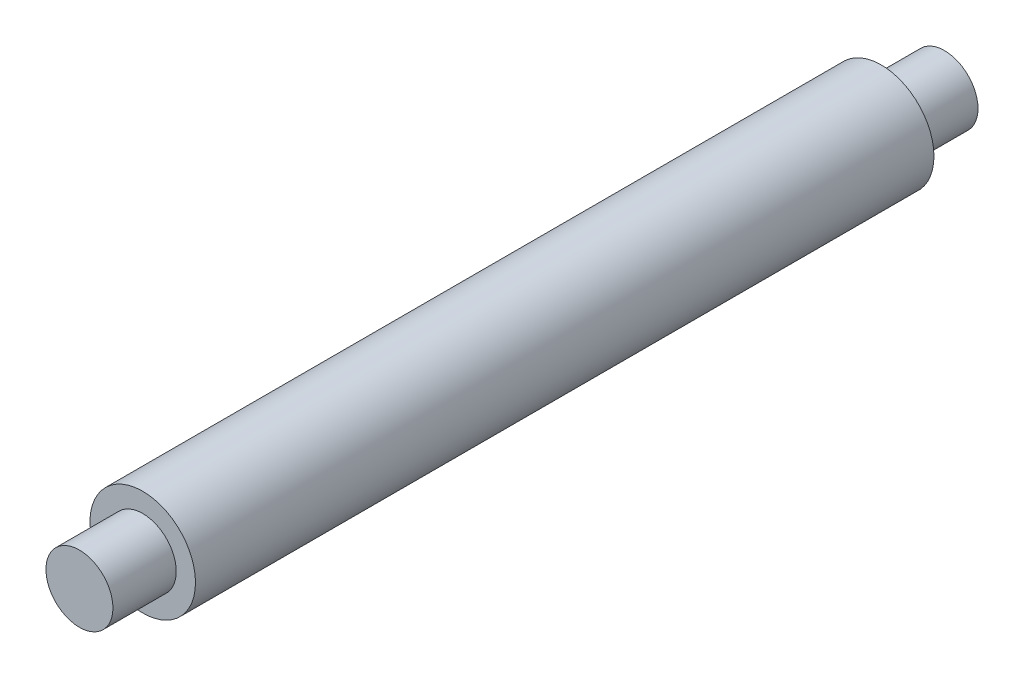
SolidWorks part; units mm, degrees
ref_plane "Front Plane" through (0, 0, 0) normal (0, 0, 1) x (1, 0, 0)
ref_plane "Top Plane" through (0, 0, 0) normal (0, 1, 0) x (1, 0, 0)
ref_plane "Right Plane" through (0, 0, 0) normal (1, 0, 0) x (0, 0, -1)
sketch "Sketch1" plane through (0, 0, 0) normal (0, 0, 1) x (1, 0, 0)
  circle A0 centre (0, 0) radius 3.175
  dimension "D1" = 6.35
extrude "Boss-Extrude1" add sketch "Sketch1" along normal mid plane 82
sketch "Sketch2" plane through (0, 0, 0) normal (0, 0, 1) x (1, 0, 0)
  circle A0 centre (0, 0) radius 5
  circle A1 centre (0, 0) radius 3.175
  circle A2 centre (0, 0) radius 3.175 construction
  dimension "D1" = 10
extrude "Boss-Extrude2" add sketch "Sketch2" along normal mid plane 70 separate body contours A0 A1
